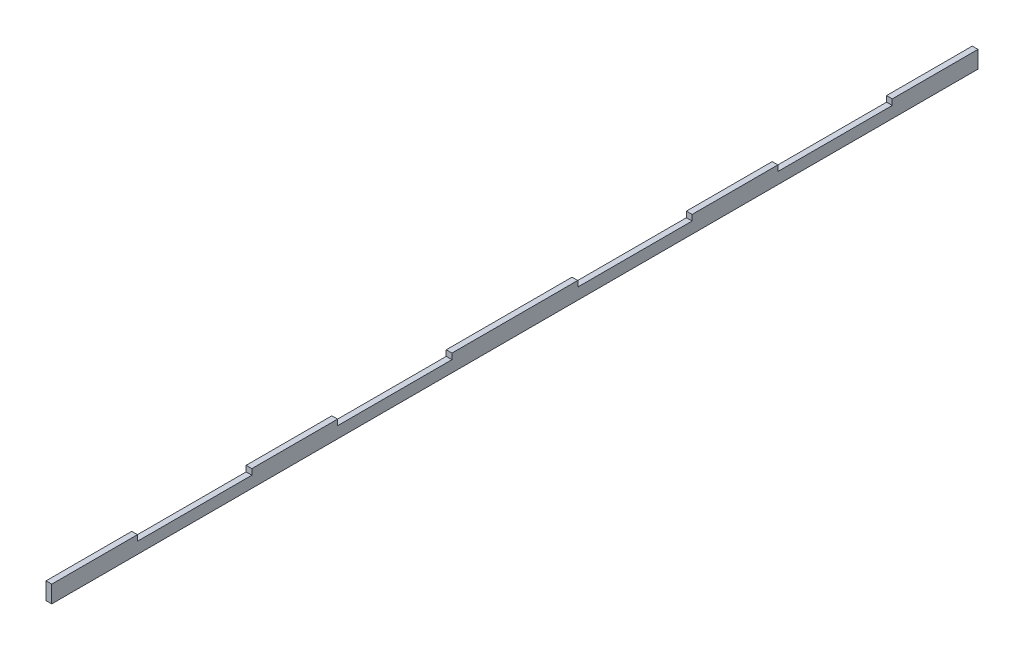
SolidWorks part; units mm, degrees
material "ABS PC"
ref_plane "Front Plane" through (0, 0, 0) normal (0, 0, 1) x (1, 0, 0)
ref_plane "Top Plane" through (0, 0, 0) normal (0, 1, 0) x (1, 0, 0)
ref_plane "Right Plane" through (0, 0, 0) normal (1, 0, 0) x (0, 0, -1)
sketch "Sketch1" plane through (0, 0, 0) normal (1, 0, 0) x (0, 0, -1)
  line L1 (-162, -3) -> (162, -3)
  line L2 (-162, -3) -> (-162, 3)
  line L3 (-162, 3) -> (162, 3)
  line L4 (162, -3) -> (162, 3)
  line L5 (-162, -3) -> (162, 3) construction
  line L6 (-162, 3) -> (162, -3) construction
  point P0 (0, 0)
  dimension "D1" = 6
  dimension "D2" = 324
extrude "Boss-Extrude1" add sketch "Sketch1" along normal blind 2
sketch "Sketch2" plane through (2, 0, 0) normal (1, 0, 0) x (0, 0, -1)
  line L0 (162, 3) -> (-162, 3) construction
  line L1 (-132, 3) -> (-92, 3)
  line L2 (-132, 3) -> (-132, 1)
  line L3 (-132, 1) -> (-92, 1)
  line L4 (-92, 3) -> (-92, 1)
  line L5 (-162, 3) -> (-162, -3) construction
  line L6 (-62, 3) -> (-22, 3)
  line L7 (-62, 3) -> (-62, 1)
  line L8 (-62, 1) -> (-22, 1)
  line L9 (-22, 3) -> (-22, 1)
  line L10 (0, 55) -> (0, -55) construction
  line L11 (62, 3) -> (62, 1)
  line L12 (62, 3) -> (22, 3)
  line L13 (22, 3) -> (22, 1)
  line L14 (62, 1) -> (22, 1)
  line L15 (132, 3) -> (132, 1)
  line L16 (132, 1) -> (92, 1)
  line L17 (132, 3) -> (92, 3)
  line L18 (92, 3) -> (92, 1)
  dimension "D1" = 30
  dimension "D2" = 2
  dimension "D3" = 40
  dimension "D4" = 30
  dimension "D5" = 2
  dimension "D6" = 40
extrude "Cut-Extrude1" cut sketch "Sketch2" against normal blind 2
